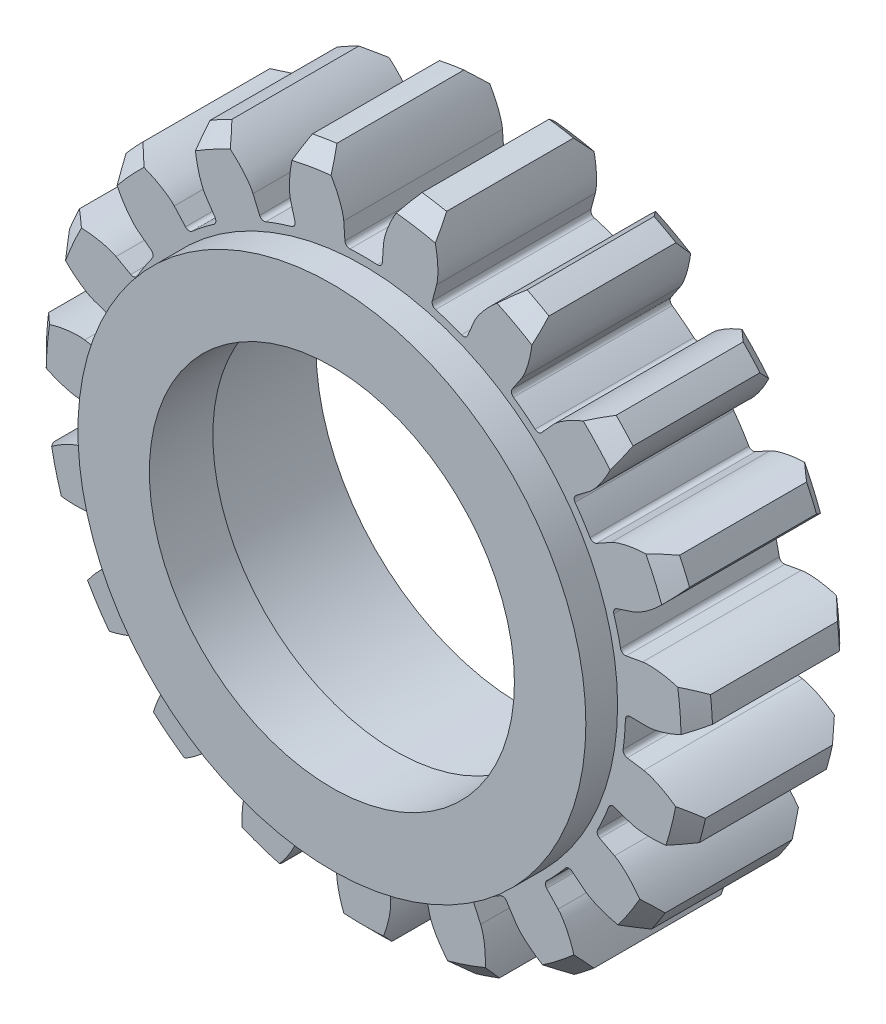
SolidWorks part; units mm, degrees
ref_plane "中间平面" through (0, 0, 0) normal (0, 0, 1) x (1, 0, 0)
ref_plane "上视基准面" through (0, 0, 0) normal (0, 1, 0) x (1, 0, 0)
ref_plane "右视基准面" through (0, 0, 0) normal (1, 0, 0) x (0, 0, -1)
sketch "直齿轮" plane through (0, 0, 0) normal (0, 0, 1) x (1, 0, 0)
  line L0 (0, 0) -> (-1.569, 18.9351) construction
  line L2 (-1.2527, 17.8102) -> (0, 0)
  line L3 (0, 0) -> (0, 52) construction
  line L4 (1.569, 18.9351) -> (0, 0) construction
  line L6 (0, 0) -> (1.2527, 17.8102)
  circle A0 centre (0, 0) radius 17.8542
  circle A1 centre (0, 0) radius 16.5
  arc A2 (1.569, 18.9351) -> (-1.569, 18.9351) centre (0, 0) ccw
  circle A3 centre (0, 0) radius 21
  spline S0 degree 4 poles (-1.2527, 17.8102) (-1.2551, 17.844) (-1.262, 17.9116) (-1.2839, 18.0457) (-1.3413, 18.2977) (-1.4438, 18.6296) (-1.622, 19.0817) (-1.8826, 19.6118) (-2.3513, 20.4075) (-3.1231, 21.4382) (-4.3729, 22.7339) (-6.2092, 24.1399) (-8.4273, 25.3786) (-10.9784, 26.3705) (-13.631, 27.0391) (-16.3413, 27.4039) (-19.2093, 27.4873) (-22.7524, 27.2198) (-26.9082, 26.3611) (-31.5415, 24.6687) (-36.3355, 22.0161) (-40.1513, 19.1175) (-43.1167, 16.2849) (-45.3725, 13.7225) (-47.044, 11.5624) (-48.5794, 9.3043) (-49.9762, 6.957) (-51.5471, 3.9273) (-53.1493, 0.1524) (-54.6038, -4.4037) (-55.4938, -8.7622) (-55.9171, -12.1429) (-56.0926, -14.5356) (-56.1598, -15.8727) (-56.1874, -17.1727) (-56.193, -18.1918) (-56.1725, -19.2684) (-56.1556, -19.8342) (-56.127, -20.5237) (-56.0985, -21.0714) (-56.0563, -21.7541) (-55.9946, -22.5814) (-55.9073, -23.5387) (-55.7864, -24.635) (-55.6447, -25.7262) (-55.4822, -26.8163) (-55.345, -27.6303) (-55.2467, -28.1725) (-55.1958, -28.443) knots 0 0 0 0 0 0.001401 0.002802 0.005604 0.010661 0.015718 0.022839 0.02996 0.048734 0.068727 0.096889 0.125051 0.153212 0.181374 0.209535 0.237696 0.271429 0.327752 0.384075 0.440398 0.496721 0.524883 0.553044 0.581206 0.609367 0.637529 0.66569 0.722013 0.778336 0.834659 0.84874 0.86282 0.876901 0.890982 0.900036 0.909091 0.914773 0.920455 0.926136 0.931818 0.943182 0.954545 0.965909 0.977273 0.988636 1 1 1 1 1 construction
  spline S1 degree 4 poles (-1.2527, 17.8102) (-1.2551, 17.844) (-1.262, 17.9116) (-1.2839, 18.0457) (-1.3413, 18.2977) (-1.4438, 18.6296) (-1.622, 19.0817) (-1.8826, 19.6118) (-2.3513, 20.4075) (-3.1231, 21.4382) (-4.3729, 22.7339) (-6.2092, 24.1399) (-8.4273, 25.3786) (-10.9784, 26.3705) (-13.631, 27.0391) (-16.3413, 27.4039) (-19.2093, 27.4873) (-22.7524, 27.2198) (-26.9082, 26.3611) (-31.5415, 24.6687) (-36.3355, 22.0161) (-40.1513, 19.1175) (-43.1167, 16.2849) (-45.3725, 13.7225) (-47.044, 11.5624) (-48.5794, 9.3043) (-49.9762, 6.957) (-51.5471, 3.9273) (-53.1493, 0.1524) (-54.6038, -4.4037) (-55.4938, -8.7622) (-55.9171, -12.1429) (-56.0926, -14.5356) (-56.1598, -15.8727) (-56.1874, -17.1727) (-56.193, -18.1918) (-56.1756, -19.1069) (-56.1653, -19.4945) (-56.1589, -19.6938) knots 0 0 0 0 0 0.001401 0.002802 0.005604 0.010661 0.015718 0.022839 0.02996 0.048734 0.068727 0.096889 0.125051 0.153212 0.181374 0.209535 0.237696 0.271429 0.327752 0.384075 0.440398 0.496721 0.524883 0.553044 0.581206 0.609367 0.637529 0.66569 0.722013 0.778336 0.834659 0.84874 0.86282 0.876901 0.890982 0.900036 0.909091 0.909091 0.909091 0.909091 0.909091
  spline S2 degree 4 poles (1.2527, 17.8102) (1.2551, 17.844) (1.262, 17.9116) (1.2839, 18.0457) (1.3413, 18.2977) (1.4438, 18.6296) (1.622, 19.0817) (1.8826, 19.6118) (2.3513, 20.4075) (3.1231, 21.4382) (4.3729, 22.7339) (6.2092, 24.1399) (8.4273, 25.3786) (10.9784, 26.3705) (13.631, 27.0391) (16.3413, 27.4039) (19.2093, 27.4873) (22.7524, 27.2198) (26.9082, 26.3611) (31.5415, 24.6687) (36.3355, 22.0161) (40.1513, 19.1175) (43.1167, 16.2849) (45.3725, 13.7225) (47.044, 11.5624) (48.5794, 9.3043) (49.9762, 6.957) (51.5471, 3.9273) (53.1493, 0.1524) (54.6038, -4.4037) (55.4938, -8.7622) (55.9171, -12.1429) (56.0926, -14.5356) (56.1598, -15.8727) (56.1874, -17.1727) (56.193, -18.1918) (56.1725, -19.2684) (56.1556, -19.8342) (56.127, -20.5237) (56.0985, -21.0714) (56.0563, -21.7541) (55.9946, -22.5814) (55.9073, -23.5387) (55.7864, -24.635) (55.6447, -25.7262) (55.4822, -26.8163) (55.345, -27.6303) (55.2467, -28.1725) (55.1958, -28.443) knots 0 0 0 0 0 0.001401 0.002802 0.005604 0.010661 0.015718 0.022839 0.02996 0.048734 0.068727 0.096889 0.125051 0.153212 0.181374 0.209535 0.237696 0.271429 0.327752 0.384075 0.440398 0.496721 0.524883 0.553044 0.581206 0.609367 0.637529 0.66569 0.722013 0.778336 0.834659 0.84874 0.86282 0.876901 0.890982 0.900036 0.909091 0.914773 0.920455 0.926136 0.931818 0.943182 0.954545 0.965909 0.977273 0.988636 1 1 1 1 1 construction
  spline S3 degree 4 poles (1.2527, 17.8102) (1.2551, 17.844) (1.262, 17.9116) (1.2839, 18.0457) (1.3413, 18.2977) (1.4438, 18.6296) (1.622, 19.0817) (1.8826, 19.6118) (2.3513, 20.4075) (3.1231, 21.4382) (4.3729, 22.7339) (6.2092, 24.1399) (8.4273, 25.3786) (10.9784, 26.3705) (13.631, 27.0391) (16.3413, 27.4039) (19.2093, 27.4873) (22.7524, 27.2198) (26.9082, 26.3611) (31.5415, 24.6687) (36.3355, 22.0161) (40.1513, 19.1175) (43.1167, 16.2849) (45.3725, 13.7225) (47.044, 11.5624) (48.5794, 9.3043) (49.9762, 6.957) (51.5471, 3.9273) (53.1493, 0.1524) (54.6038, -4.4037) (55.4938, -8.7622) (55.9171, -12.1429) (56.0926, -14.5356) (56.1598, -15.8727) (56.1874, -17.1727) (56.193, -18.1918) (56.1756, -19.1069) (56.1653, -19.4945) (56.1589, -19.6938) knots 0 0 0 0 0 0.001401 0.002802 0.005604 0.010661 0.015718 0.022839 0.02996 0.048734 0.068727 0.096889 0.125051 0.153212 0.181374 0.209535 0.237696 0.271429 0.327752 0.384075 0.440398 0.496721 0.524883 0.553044 0.581206 0.609367 0.637529 0.66569 0.722013 0.778336 0.834659 0.84874 0.86282 0.876901 0.890982 0.900036 0.909091 0.909091 0.909091 0.909091 0.909091
  dimension "基圆直径" = 35.7083
  dimension "齿根圆" = 33
  dimension "分度圆" = 38
  dimension "齿顶圆" = 42
  dimension "D1" = 3.1416
sketch "圆" plane through (0, 0, 0) normal (0, 0, 1) x (1, 0, 0)
  circle A0 centre (0, 0) radius 21 construction
  circle A1 centre (0, 0) radius 21
extrude "毛胚" add sketch "圆" along normal mid plane 10
chamfer "轮齿倒角" distance 1 angle 45 2 edges at (21, 0, -5) (21, 0, 5)
sketch "齿形" plane through (0, 0, 0) normal (0, 0, 1) x (1, 0, 0)
  line L4 (0, 0) -> (1.2527, 17.8102) construction
  line L5 (-1.2527, 17.8102) -> (0, 0) construction
  line L6 (0, 0) -> (1.2527, 17.8102)
  line L7 (-1.2527, 17.8102) -> (0, 0)
  circle A4 centre (0, 0) radius 16.5 construction
  circle A5 centre (0, 0) radius 21 construction
  circle A6 centre (0, 0) radius 16.5
  circle A7 centre (0, 0) radius 21
  spline S1 degree 4 poles (-998.091, 43.7983) (30.746, 11.7394) (1.8294, 14.6629) (0.9419, 16.5452) (1.3413, 18.2977) (1.4438, 18.6296) (1.622, 19.0817) (1.8826, 19.6118) (2.3513, 20.4075) (3.1231, 21.4382) (4.3729, 22.7339) (6.2092, 24.1399) (8.4273, 25.3786) (10.9784, 26.3705) (13.631, 27.0391) (16.3413, 27.4039) (19.2093, 27.4873) (22.7524, 27.2198) (26.9082, 26.3611) (31.5415, 24.6687) (36.3355, 22.0161) (40.1513, 19.1175) (43.1167, 16.2849) (45.3725, 13.7225) (47.044, 11.5624) (48.5794, 9.3043) (49.9762, 6.957) (51.5471, 3.9273) (53.1493, 0.1524) (54.6038, -4.4037) (55.4938, -8.7622) (55.9171, -12.1429) (56.0926, -14.5356) (56.1598, -15.8727) (56.1874, -17.1727) (56.2046, -20.3249) (55.8786, -26.481) (56.9168, 14.6594) (23.0461, -1019.0526) knots -0.063477 -0.063477 -0.063477 -0.063477 -0.063477 0.001401 0.002802 0.005604 0.010661 0.015718 0.022839 0.02996 0.048734 0.068727 0.096889 0.125051 0.153212 0.181374 0.209535 0.237696 0.271429 0.327752 0.384075 0.440398 0.496721 0.524883 0.553044 0.581206 0.609367 0.637529 0.66569 0.722013 0.778336 0.834659 0.84874 0.86282 0.876901 0.890982 0.900036 1.00595 1.00595 1.00595 1.00595 1.00595 only from (1.2527, 17.8102) to (56.1589, -19.6938) construction
  spline S3 degree 4 poles (998.091, 43.7983) (-30.746, 11.7394) (-1.8294, 14.6629) (-0.9419, 16.5452) (-1.3413, 18.2977) (-1.4438, 18.6296) (-1.622, 19.0817) (-1.8826, 19.6118) (-2.3513, 20.4075) (-3.1231, 21.4382) (-4.3729, 22.7339) (-6.2092, 24.1399) (-8.4273, 25.3786) (-10.9784, 26.3705) (-13.631, 27.0391) (-16.3413, 27.4039) (-19.2093, 27.4873) (-22.7524, 27.2198) (-26.9082, 26.3611) (-31.5415, 24.6687) (-36.3355, 22.0161) (-40.1513, 19.1175) (-43.1167, 16.2849) (-45.3725, 13.7225) (-47.044, 11.5624) (-48.5794, 9.3043) (-49.9762, 6.957) (-51.5471, 3.9273) (-53.1493, 0.1524) (-54.6038, -4.4037) (-55.4938, -8.7622) (-55.9171, -12.1429) (-56.0926, -14.5356) (-56.1598, -15.8727) (-56.1874, -17.1727) (-56.2046, -20.3249) (-55.8786, -26.481) (-56.9168, 14.6594) (-23.0461, -1019.0526) knots -0.063477 -0.063477 -0.063477 -0.063477 -0.063477 0.001401 0.002802 0.005604 0.010661 0.015718 0.022839 0.02996 0.048734 0.068727 0.096889 0.125051 0.153212 0.181374 0.209535 0.237696 0.271429 0.327752 0.384075 0.440398 0.496721 0.524883 0.553044 0.581206 0.609367 0.637529 0.66569 0.722013 0.778336 0.834659 0.84874 0.86282 0.876901 0.890982 0.900036 1.00595 1.00595 1.00595 1.00595 1.00595 only from (-1.2527, 17.8102) to (-56.1589, -19.6938) construction
  spline S4 degree 4 poles (1.2527, 17.8102) (1.2551, 17.844) (1.262, 17.9116) (1.2839, 18.0457) (1.3413, 18.2977) (1.4438, 18.6296) (1.622, 19.0817) (1.8826, 19.6118) (2.3513, 20.4075) (3.1231, 21.4382) (4.3729, 22.7339) (6.2092, 24.1399) (8.4273, 25.3786) (10.9784, 26.3705) (13.631, 27.0391) (16.3413, 27.4039) (19.2093, 27.4873) (22.7524, 27.2198) (26.9082, 26.3611) (31.5415, 24.6687) (36.3355, 22.0161) (40.1513, 19.1175) (43.1167, 16.2849) (45.3725, 13.7225) (47.044, 11.5624) (48.5794, 9.3043) (49.9762, 6.957) (51.5471, 3.9273) (53.1493, 0.1524) (54.6038, -4.4037) (55.4938, -8.7622) (55.9171, -12.1429) (56.0926, -14.5356) (56.1598, -15.8727) (56.1874, -17.1727) (56.193, -18.1918) (56.1756, -19.1069) (56.1653, -19.4945) (56.1589, -19.6938) knots 0 0 0 0 0 0.001401 0.002802 0.005604 0.010661 0.015718 0.022839 0.02996 0.048734 0.068727 0.096889 0.125051 0.153212 0.181374 0.209535 0.237696 0.271429 0.327752 0.384075 0.440398 0.496721 0.524883 0.553044 0.581206 0.609367 0.637529 0.66569 0.722013 0.778336 0.834659 0.84874 0.86282 0.876901 0.890982 0.900036 0.909091 0.909091 0.909091 0.909091 0.909091
  spline S5 degree 4 poles (-1.2527, 17.8102) (-1.2551, 17.844) (-1.262, 17.9116) (-1.2839, 18.0457) (-1.3413, 18.2977) (-1.4438, 18.6296) (-1.622, 19.0817) (-1.8826, 19.6118) (-2.3513, 20.4075) (-3.1231, 21.4382) (-4.3729, 22.7339) (-6.2092, 24.1399) (-8.4273, 25.3786) (-10.9784, 26.3705) (-13.631, 27.0391) (-16.3413, 27.4039) (-19.2093, 27.4873) (-22.7524, 27.2198) (-26.9082, 26.3611) (-31.5415, 24.6687) (-36.3355, 22.0161) (-40.1513, 19.1175) (-43.1167, 16.2849) (-45.3725, 13.7225) (-47.044, 11.5624) (-48.5794, 9.3043) (-49.9762, 6.957) (-51.5471, 3.9273) (-53.1493, 0.1524) (-54.6038, -4.4037) (-55.4938, -8.7622) (-55.9171, -12.1429) (-56.0926, -14.5356) (-56.1598, -15.8727) (-56.1874, -17.1727) (-56.193, -18.1918) (-56.1756, -19.1069) (-56.1653, -19.4945) (-56.1589, -19.6938) knots 0 0 0 0 0 0.001401 0.002802 0.005604 0.010661 0.015718 0.022839 0.02996 0.048734 0.068727 0.096889 0.125051 0.153212 0.181374 0.209535 0.237696 0.271429 0.327752 0.384075 0.440398 0.496721 0.524883 0.553044 0.581206 0.609367 0.637529 0.66569 0.722013 0.778336 0.834659 0.84874 0.86282 0.876901 0.890982 0.900036 0.909091 0.909091 0.909091 0.909091 0.909091
extrude "插齿" cut sketch "齿形" against normal mid plane 10 contours S5 A6 S4 A7
fillet "圆角1" [suppressed] radius 0.3
pattern_circular "圆周阵列1" [suppressed] count 19 over 360
fillet "圆角2" radius 0.3 2 edges at (1.1577, 16.4593, 0) (-1.1577, 16.4593, 0)
pattern_circular "圆周阵列2" count 19 over 360 about axis through (0, 0, 5) along (0, 0, -1) of "圆角2", "插齿"
sketch "分度圆" plane through (0, 0, 0) normal (0, 0, 1) x (1, 0, 0)
  circle A0 centre (0, 0) radius 19 construction
  circle A1 centre (0, 0) radius 19 construction
sketch "草图1" plane through (0, 0, 5) normal (0, 0, 1) x (1, 0, 0)
  circle A0 centre (0, 0) radius 16
  dimension "D1" = 32
extrude "凸台-拉伸1" add sketch "草图1" along normal blind 2
sketch "草图2" plane through (0, 0, 7) normal (0, 0, 1) x (1, 0, 0)
  circle A0 centre (0, 0) radius 11.5
  dimension "D1" = 23
extrude "切除-拉伸1" cut sketch "草图2" against normal through all
sketch "草图3" plane through (0, 0, -5) normal (0, 0, -1) x (-1, 0, 0)
  circle A0 centre (0, 0) radius 13
  dimension "D1" = 26
extrude "切除-拉伸2" cut sketch "草图3" against normal blind 8
equation "\"m\"= 2'模数"
equation "\"z\" = 19'齿数"
equation "\"a\"= 20'压力角（常见为20°）"
equation "\"B\"= 10'齿宽"
equation "\"C1\"= 1'轮齿倒角（若设为0，则无倒角）"
equation "\"x\"= 0'变位系数（不懂勿动）"
equation "\"ha\"= 1'齿顶高系数（不懂勿动）"
equation "\"c\"= 0.25'顶隙系数（不懂勿动）"
equation "\"基圆直径@直齿轮\"= \"m\" * \"z\" * cos ( \"a\" )"
equation "\"齿根圆@直齿轮\" = \"m\" * ( \"z\" - 2 * ( \"ha\" - \"x\" + \"c\" ) )"
equation "\"分度圆@直齿轮\"=\"m\" * \"z\""
equation "\"齿顶圆@直齿轮\" = \"m\" * ( \"z\" + 2 * ( \"ha\" + \"x\" ) )"
equation "\"R\"= 0.3'齿根圆角"
equation "\"D1\"= \"R\""
equation "\"D1@毛胚\" = \"B\""
equation "\"D1@轮齿倒角\" = IIF ( \"C1\" > 0 , \"C1\" , 0.001 )"
equation "\"轮齿倒角\"= IIF ( \"C1\" > 0 , \"unsuppressed\" , \"suppressed\" )"
equation "\"D1@插齿\" = \"B\""
equation "\"D1@圆周阵列1\" = \"z\""
equation "\"D1@直齿轮\"= \"m\" * ( pi / 2 ) - 2 * \"m\" * tan ( \"a\" ) * \"x\"'作者：机械菌-"
equation "\"D1@圆角1\"=\"R\""
equation "\"圆角1\" = IIF ( \"m\" * ( \"z\" - 2 * ( \"ha\" - \"x\" + \"c\" ) ) > \"m\" * \"z\" * cos ( \"a\" ) , \"unsuppressed\" , \"suppressed\" )"
equation "\"圆周阵列1\"= IIF ( \"m\" * ( \"z\" - 2 * ( \"ha\" - \"x\" + \"c\" ) ) > \"m\" * \"z\" * cos ( \"a\" ) , \"unsuppressed\" , \"suppressed\" )"
equation "\"D1@圆角2\"=\"R\""
equation "\"D1@圆周阵列2\" = \"z\""
equation "\"圆角2\" = IIF ( \"m\" * ( \"z\" - 2 * ( \"ha\" - \"x\" + \"c\" ) ) < \"m\" * \"z\" * cos ( \"a\" ) , \"unsuppressed\" , \"suppressed\" )"
equation "\"圆周阵列2\"= IIF ( \"m\" *  ( \"z\" - 2 *  ( \"ha\" - \"x\" + \"c\" )  )  < \"m\" * \"z\" * cos ( \"a\" )  ,  unsuppressed  ,  suppressed  ) "
